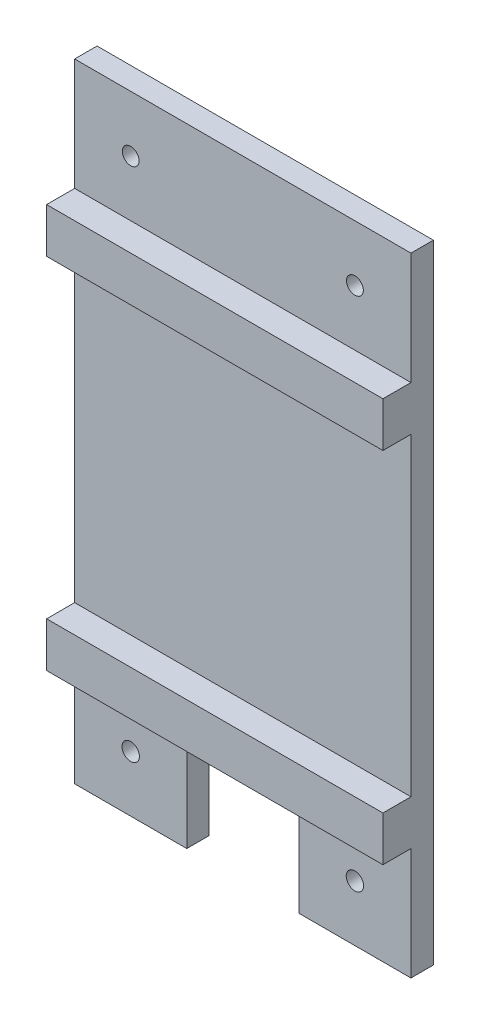
SolidWorks part; units mm, degrees
ref_plane "Alzado" through (0, 0, 0) normal (0, 0, 1) x (1, 0, 0)
ref_plane "Planta" through (0, 0, 0) normal (0, 1, 0) x (1, 0, 0)
ref_plane "Vista lateral" through (0, 0, 0) normal (1, 0, 0) x (0, 0, -1)
sketch "Croquis1" plane through (0, 0, 0) normal (0, 0, 1) x (1, 0, 0)
  line L0 (-30, -56) -> (-10, -56)
  line L1 (-30, -56) -> (-10, -56)
  line L2 (-30, -56) -> (-30, 56)
  line L3 (-30, 56) -> (30, 56)
  line L4 (30, -56) -> (30, 56)
  line L5 (-30, -56) -> (30, 56) construction
  line L6 (-30, 56) -> (30, -56) construction
  line L7 (-10, -56) -> (-10, -36)
  line L8 (-10, -36) -> (10, -36)
  line L9 (10, -36) -> (10, -56)
  line L10 (10, -56) -> (30, -56)
  line L11 (10, -56) -> (30, -56)
  point P0 (0, 0)
  dimension "D1" = 60
  dimension "D2" = 112
  dimension "D3" = 20
  dimension "D4" = 20
  dimension "D5" = 20
extrude "Saliente-Extruir1" add sketch "Croquis1" along normal blind 4 contours L9 L10 L4 L3 L2 L0 L7 L8
sketch "Croquis2" plane through (0, 0, 4) normal (0, 0, 1) x (1, 0, 0)
  line L0 (-30, -36) -> (30, -36)
  line L2 (30, -56) -> (30, 56) construction
  line L3 (30, -36) -> (30, -28)
  line L4 (30, -28) -> (-30, -28)
  line L5 (-30, -56) -> (-30, 56) construction
  line L6 (-30, -28) -> (-30, -36)
  line L7 (30, -28) -> (30, 28)
  line L8 (30, 28) -> (-30, 28)
  line L9 (-30, 28) -> (-30, 36)
  line L10 (-30, 36) -> (30, 36)
  line L11 (30, 36) -> (30, 28)
  point P3 (0, -36)
  line M6 (30, -56) -> (30, 56)
  line M8 (-30, 56) -> (-30, -56)
  dimension "D1" = 8
  dimension "D2" = 56
  dimension "D3" = 8
extrude "Saliente-Extruir2" add sketch "Croquis2" along normal blind 5 contours L10 L8 M8 M6 | L4 L6 L0 L3
sketch "Croquis3" plane through (0, 0, 4) normal (0, 0, 1) x (1, 0, 0)
  line L0 (-20, -56) -> (-20, -36) construction
  line L1 (-30, -56) -> (-10, -56) construction
  line L2 (-30, -36) -> (-10, -36) construction
  line L3 (20, -56) -> (20, -36) construction
  line L4 (10, -56) -> (30, -56) construction
  line L5 (10, -36) -> (30, -36) construction
  line L6 (20, 36) -> (20, 56) construction
  line L7 (-30, 56) -> (30, 56) construction
  line L8 (30, 36) -> (-30, 36) construction
  line L9 (-20, 36) -> (-20, 56) construction
  circle A0 centre (-20, -46) radius 1.55
  circle A1 centre (20, -46) radius 1.55
  circle A2 centre (-20, 46) radius 1.5
  circle A3 centre (20, 46) radius 1.5
  dimension "D1" = 3.1
  dimension "D2" = 3
  dimension "D3" = 3
extrude "Cortar-Extruir1" cut sketch "Croquis3" against normal through all
